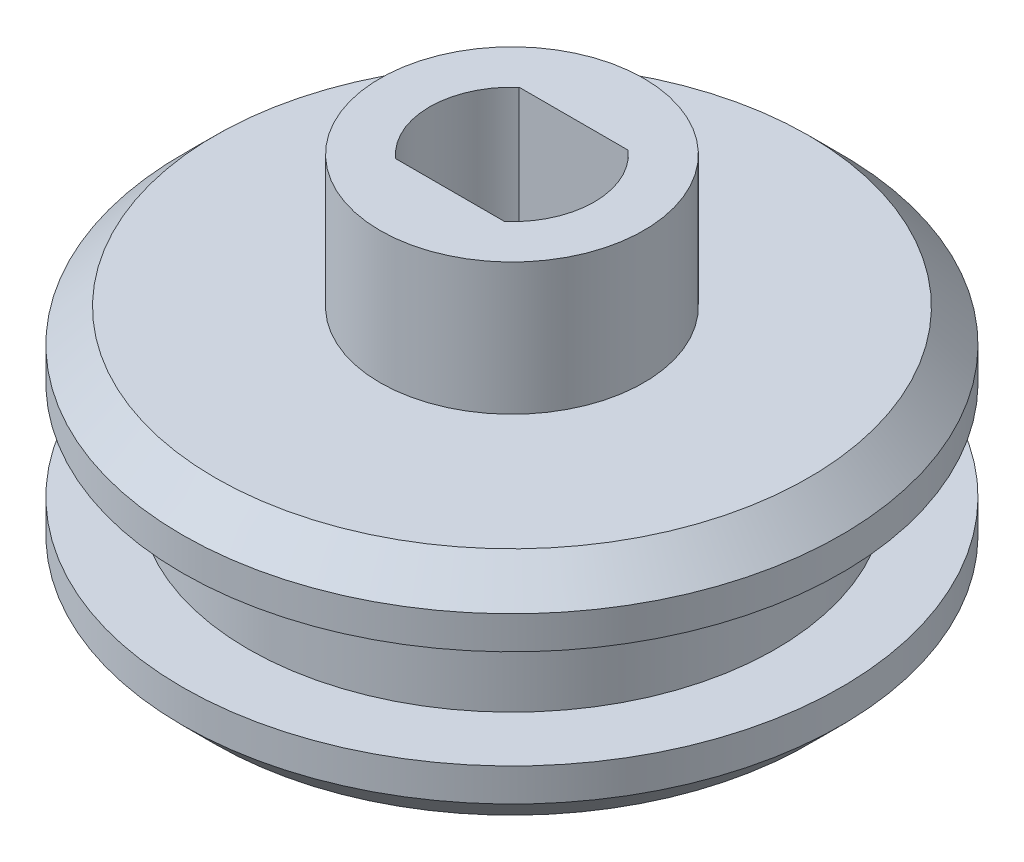
SolidWorks part; units mm, degrees
ref_plane "Alzado" through (0, 0, 0) normal (0, 0, 1) x (1, 0, 0)
ref_plane "Planta" through (0, 0, 0) normal (0, 1, 0) x (1, 0, 0)
ref_plane "Vista lateral" through (0, 0, 0) normal (1, 0, 0) x (0, 0, -1)
sketch "Croquis1" plane through (0, 0, 0) normal (0, 1, 0) x (1, 0, 0)
  circle A3 centre (0, 0) radius 10
  dimension "D1" = 20
extrude "Saliente-Extruir1" add sketch "Croquis1" along normal blind 2
sketch "Croquis4" plane through (0, 2, 0) normal (0, 1, 0) x (1, 0, 0)
  circle A0 centre (0, 0) radius 8
  dimension "D1" = 16
extrude "Saliente-Extruir2" add sketch "Croquis4" along normal blind 3
sketch "Croquis5" plane through (0, 5, 0) normal (0, 1, 0) x (1, 0, 0)
  circle A0 centre (0, 0) radius 10
  circle A1 centre (0, 0) radius 10 construction
extrude "Saliente-Extruir3" add sketch "Croquis5" along normal blind 2
chamfer "Chaflán1" distance 1 angle 45 1 edges at (0, 7, 10)
chamfer "Chaflán2" distance 1 angle 45 1 edges at (0, 0, 10)
sketch "Croquis7" plane through (0, 7, 0) normal (0, 1, 0) x (1, 0, 0)
  circle A0 centre (0, 0) radius 4
  dimension "D1" = 8
extrude "Saliente-Extruir4" add sketch "Croquis7" along normal blind 4
sketch "Croquis6" plane through (0, 7, 0) normal (0, 1, 0) x (1, 0, 0)
  line L1 (-1.6536, -1.875) -> (1.6536, -1.875)
  line L3 (-1.6536, 1.875) -> (1.6536, 1.875)
  line L5 (-2.2972, -0.9864) -> (2.2972, 0.9864) construction
  line L6 (-2.2972, 0.9864) -> (2.2972, -0.9864) construction
  arc A0 (-1.6536, 1.875) -> (-1.6536, -1.875) centre (0, 0) ccw
  arc A1 (1.6536, -1.875) -> (1.6536, 1.875) centre (0, 0) ccw
  dimension "D1" = 5
extrude "Cortar-Extruir1" cut sketch "Croquis6" along normal through all
sketch "Croquis8" plane through (0, 0, 0) normal (0, -1, 0) x (1, 0, 0)
  circle A0 centre (0, 0) radius 1
  dimension "D1" = 2
extrude "Cortar-Extruir2" cut sketch "Croquis8" against normal through all
sketch "Croquis9" plane through (0, 0, 0) normal (0, -1, 0) x (1, 0, 0)
  circle A0 centre (0, 0) radius 2.5
  dimension "D1" = 5
extrude "Cortar-Extruir3" cut sketch "Croquis9" against normal blind 5
